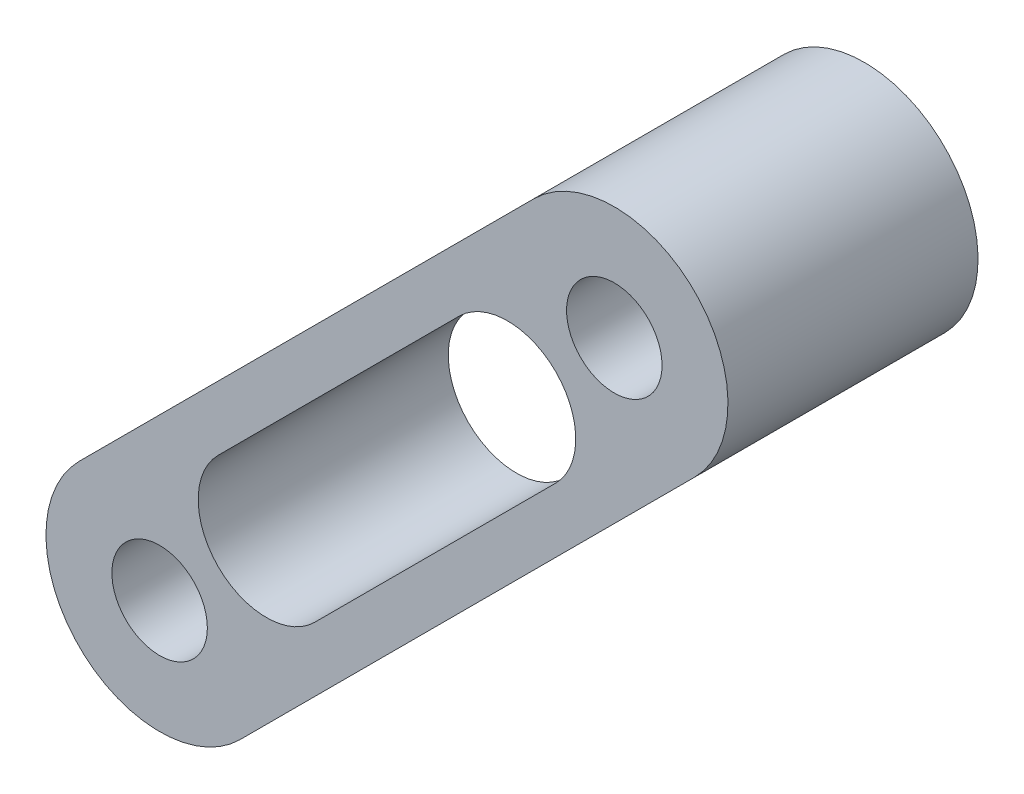
SolidWorks part; units mm, degrees
ref_plane "Plan de face" through (0, 0, 0) normal (0, 0, 1) x (1, 0, 0)
ref_plane "Plan de dessus" through (0, 0, 0) normal (0, 1, 0) x (1, 0, 0)
ref_plane "Plan de droite" through (0, 0, 0) normal (1, 0, 0) x (0, 0, -1)
sketch "Esquisse1" plane through (0, 0, 0) normal (0, 0, 1) x (1, 0, 0)
  line L0 (0, 0) -> (-20, 0) construction
  line L1 (-20, 0) -> (0, 20) construction
  line L2 (-23.5355, 3.5355) -> (-3.5355, 23.5355)
  line L3 (-16.4645, -3.5355) -> (3.5355, 16.4645)
  line L4 (-15.3033, 4.6967) -> (-4.6967, 15.3033) construction
  line L5 (-17.4246, 6.818) -> (-6.818, 17.4246)
  line L6 (-13.182, 2.5754) -> (-2.5754, 13.182)
  circle A0 centre (-20, 0) radius 2.1
  circle A1 centre (0, 0) radius 20 construction
  circle A2 centre (0, 20) radius 2.1
  arc A3 (-23.5355, 3.5355) -> (-16.4645, -3.5355) centre (-20, 0) ccw
  arc A4 (3.5355, 16.4645) -> (-3.5355, 23.5355) centre (0, 20) ccw
  arc A5 (-17.4246, 6.818) -> (-13.182, 2.5754) centre (-15.3033, 4.6967) ccw
  arc A6 (-2.5754, 13.182) -> (-6.818, 17.4246) centre (-4.6967, 15.3033) ccw
  point P7 (-10, 10)
  point P14 (-10, 10)
  point P19 (-2.1578, 13.1811)
  dimension "D1" = 4.2
  dimension "D2" = 40
  dimension "D3" = 4.2
  dimension "D4" = 10
  dimension "D5" = 6
  dimension "D6" = 15
extrude "Boss.-Extru.1" add sketch "Esquisse1" along normal blind 11
